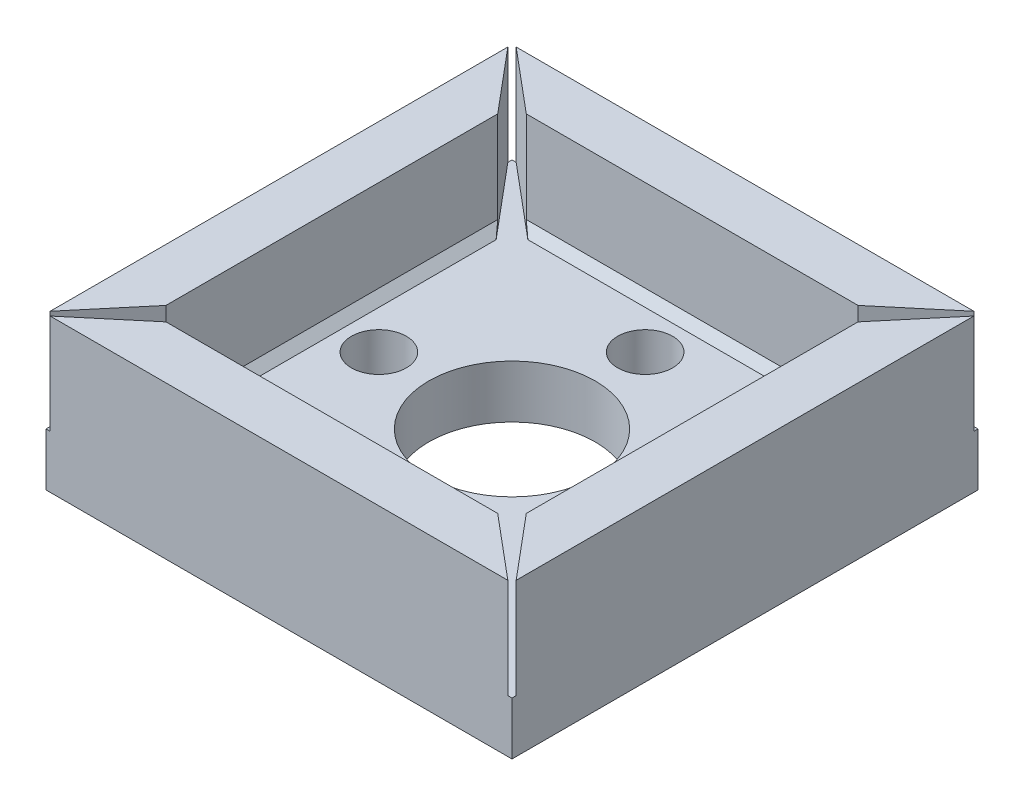
SolidWorks part; units mm, degrees
ref_plane "Front Plane" through (0, 0, 0) normal (0, 0, 1) x (1, 0, 0)
ref_plane "Top Plane" through (0, 0, 0) normal (0, 1, 0) x (1, 0, 0)
ref_plane "Right Plane" through (0, 0, 0) normal (1, 0, 0) x (0, 0, -1)
sketch "Sketch1" plane through (0, 0, 0) normal (0, 1, 0) x (1, 0, 0)
  line L1 (-14, -14) -> (14, -14)
  line L2 (-14, -14) -> (-14, 14)
  line L3 (-14, 14) -> (14, 14)
  line L4 (14, -14) -> (14, 14)
  line L5 (-14, -14) -> (14, 14) construction
  line L6 (-14, 14) -> (14, -14) construction
  point P0 (0, 0)
  dimension "D1" = 28
extrude "Boss-Extrude1" add sketch "Sketch1" along normal blind 3.175
sketch "Sketch2" plane through (0, 3.175, 0) normal (0, 1, 0) x (1, 0, 0)
  circle A0 centre (0, 0) radius 5
  dimension "D1" = 10
extrude "Cut-Extrude1" cut sketch "Sketch2" against normal through all
hole_wizard "Ø3.0mm Dowel Hole1" positions "Sketch3" profile "Sketch4" hole size "Ø3.0" standard "ANSI Metric"
sketch "Sketch3" plane through (0, 3.175, 0) normal (0, 1, 0) x (1, 0, 0)
  point P0 (8, 0)
  point P3 (0, -8)
  point P6 (-8, 0)
  point P9 (0, 8)
sketch "Sketch4" plane through (8, 3.175, 0) normal (1, 0, 0) x (0, 0, 1)
  line L0 (0, 0) -> (0, 15.9914)
  line L1 (0, 15.9914) -> (1.65, 15)
  line L2 (1.65, 15) -> (1.65, 0)
  line L5 (1.65, 0) -> (0, 0)
  line L10 (0, 15.9914) -> (-1.65, 15) construction
  line L11 (0, -6.35) -> (0, 107.95) construction
  dimension "Hole Dia." = 3.3
  dimension "Hole Depth" = 15
  dimension "Drill Angle" = 118
sketch "Sketch7" plane through (0, 3.175, 0) normal (0, 1, 0) x (1, 0, 0)
  line L0 (-13.75, -14) -> (13.75, -14)
  line L1 (13.75, -14) -> (9.9662, -10.825)
  line L2 (9.9662, -10.825) -> (-9.9662, -10.825)
  line L3 (-13.75, -14) -> (-9.9662, -10.825)
  line L4 (-14, 14) -> (-14, -14) construction
  line L5 (14, -14) -> (14, 14) construction
  line L6 (-14, -14) -> (14, -14) construction
  point P2 (0, -14)
  point P3 (0, -14)
  point P7 (-9.6206, -9.8597)
  point P11 (0, 0)
  point P12 (0, 0)
  point P13 (-11.763, -13)
  point P16 (11.7029, -13)
  point P17 (-13, -13)
  point P19 (0, 0)
  point P20 (0, 0)
  point P21 (0, 0)
  point P22 (0, 0)
  dimension "D1" = 3.175
  dimension "D2" = 50
  dimension "D3" = 50
  dimension "D4" = 0.25
extrude "Boss-Extrude3" add sketch "Sketch7" along normal blind 6
pattern_circular "CirPattern2" count 4 over 360 about axis through (0, 0, 0) along (0, 1, 0) of "Boss-Extrude3"
chamfer "Chamfer2" distance 0.5 angle 45 4 edges at (0, 3.175, 10.825) (10.825, 3.175, 0) (0, 3.175, -10.825) (-10.825, 3.175, 0)
